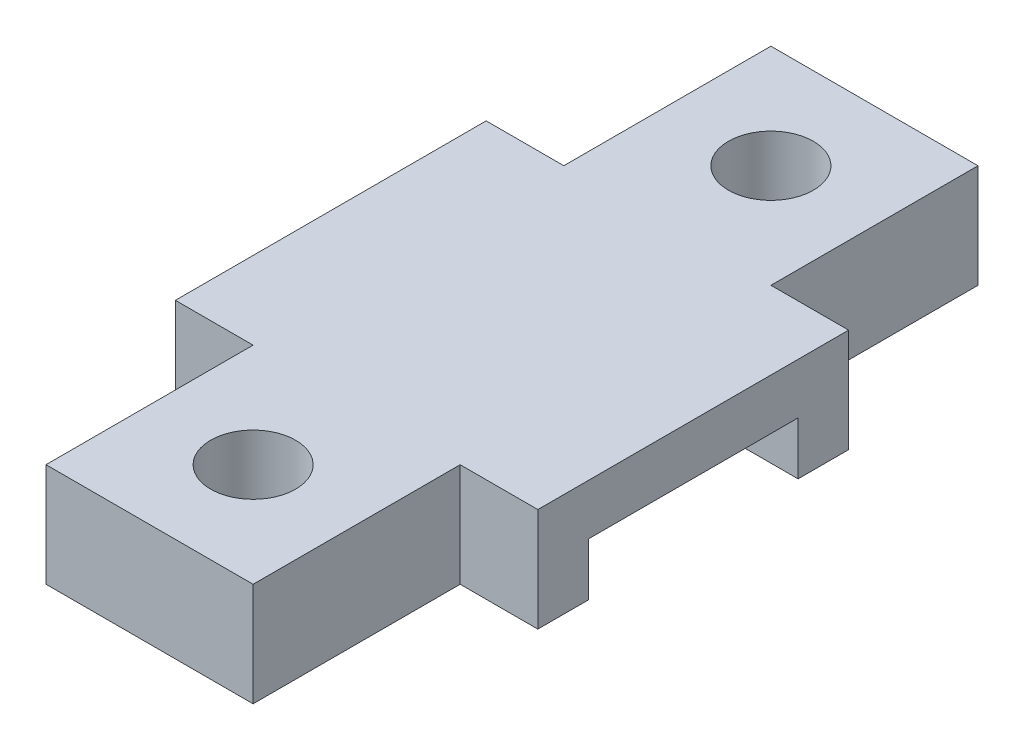
SolidWorks part; units mm, degrees
ref_plane "Спереди" through (0, 0, 0) normal (0, 0, 1) x (1, 0, 0)
ref_plane "Сверху" through (0, 0, 0) normal (0, 1, 0) x (1, 0, 0)
ref_plane "Справа" through (0, 0, 0) normal (1, 0, 0) x (0, 0, -1)
sketch "Sketch1" plane through (0, 0, 0) normal (0, 1, 0) x (1, 0, 0)
  line L1 (10, -35) -> (-10, -35)
  line L2 (10, -35) -> (10, 35)
  line L3 (10, 35) -> (-10, 35)
  line L4 (-10, -35) -> (-10, 35)
  line L5 (10, -35) -> (-10, 35) construction
  line L6 (10, 35) -> (-10, -35) construction
  point P0 (0, 0)
  dimension "D1" = 20
  dimension "D2" = 70
extrude "Boss-Extrude1" add sketch "Sketch1" along normal blind 10
sketch "Sketch2" plane through (10, 0, 0) normal (1, 0, 0) x (0, 0, -1)
  line L0 (0, 0) -> (0, 10) construction
  line L1 (-35, 0) -> (35, 0) construction
  line L2 (-35, 10) -> (35, 10) construction
  line L4 (10.125, 5.1) -> (-10.125, 5.1)
  line L5 (10.125, 5.1) -> (10.125, 0)
  line L6 (10.125, 0) -> (-10.125, 0)
  line L7 (-10.125, 5.1) -> (-10.125, 0)
  line L8 (10.125, 5.1) -> (-10.125, 0) construction
  line L9 (10.125, 0) -> (-10.125, 5.1) construction
  point P6 (0, 2.55)
  dimension "D1" = 20.25
  dimension "D2" = 5.1
extrude "Cut-Extrude1" cut sketch "Sketch2" against normal through all and the other way through all
sketch "Sketch3" plane through (0, 0, 0) normal (0, -1, 0) x (1, 0, 0)
  line L0 (0, 35) -> (0, -35) construction
  line L1 (-10, 35) -> (10, 35) construction
  line L2 (10, -35) -> (-10, -35) construction
  circle A0 centre (0, 25) radius 4.1
  circle A1 centre (0, -25) radius 4.1
  dimension "D1" = 8.2
  dimension "D2" = 25
  dimension "D3" = 50
extrude "Cut-Extrude2" cut sketch "Sketch3" against normal through all
sketch "Sketch4" plane through (10, 0, 0) normal (1, 0, 0) x (0, 0, -1)
  line L0 (-10.125, 0) -> (-15.005, 0)
  line L1 (-35, 0) -> (-10.125, 0) construction
  line L2 (-15.005, 0) -> (-15.005, 10)
  line L3 (-35, 10) -> (35, 10) construction
  line L4 (-15.005, 10) -> (15.005, 10)
  line L5 (15.005, 10) -> (15.005, 0)
  line L6 (10.125, 0) -> (35, 0) construction
  line L7 (15.005, 0) -> (10.125, 0)
  line L8 (10.125, 0) -> (10.125, 5.1)
  line L9 (10.125, 5.1) -> (-10.125, 5.1)
  line L10 (-10.125, 5.1) -> (-10.125, 0)
  dimension "D1" = 4.88
extrude "Boss-Extrude2" add sketch "Sketch4" along normal blind 7.5 and the other way blind 27.5
